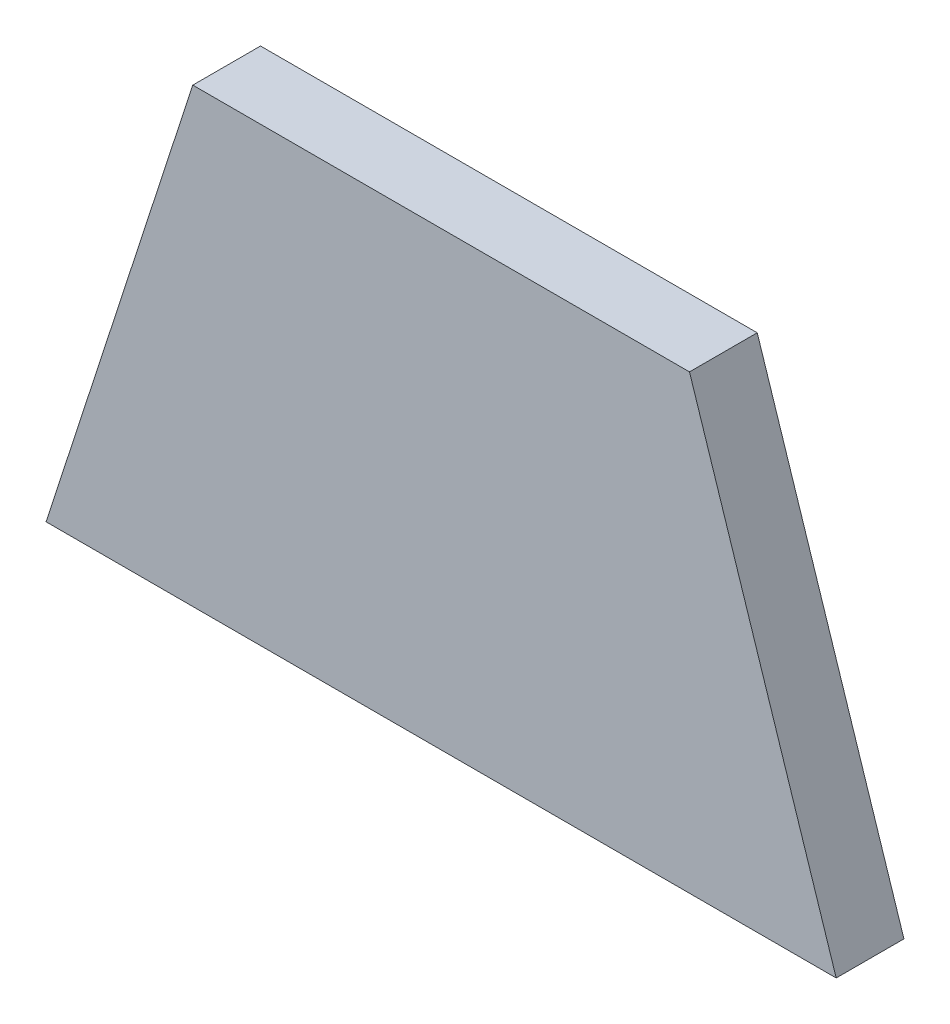
SolidWorks part; units mm, degrees
ref_plane "Front" through (0, 0, 0) normal (0, 0, 1) x (1, 0, 0)
ref_plane "Top" through (0, 0, 0) normal (0, 1, 0) x (1, 0, 0)
ref_plane "Right" through (0, 0, 0) normal (1, 0, 0) x (0, 0, -1)
sketch "Esquisse1" plane through (0, 0, 0) normal (0, 0, 1) x (1, 0, 0)
  line L0 (0, 0) -> (174.9839, 0)
  line L1 (87.492, 0) -> (87.492, 100) construction
  line L2 (142.492, 100) -> (32.492, 100)
  line L3 (32.492, 100) -> (0, 0)
  line L4 (142.492, 100) -> (174.9839, 0)
  point P7 (0, 0)
  point P8 (119.0551, 0)
  dimension "D1" = 36
  dimension "D2" = 100
  dimension "D3" = 110
extrude "Boss.-Extru.1" add sketch "Esquisse1" along normal blind 15
